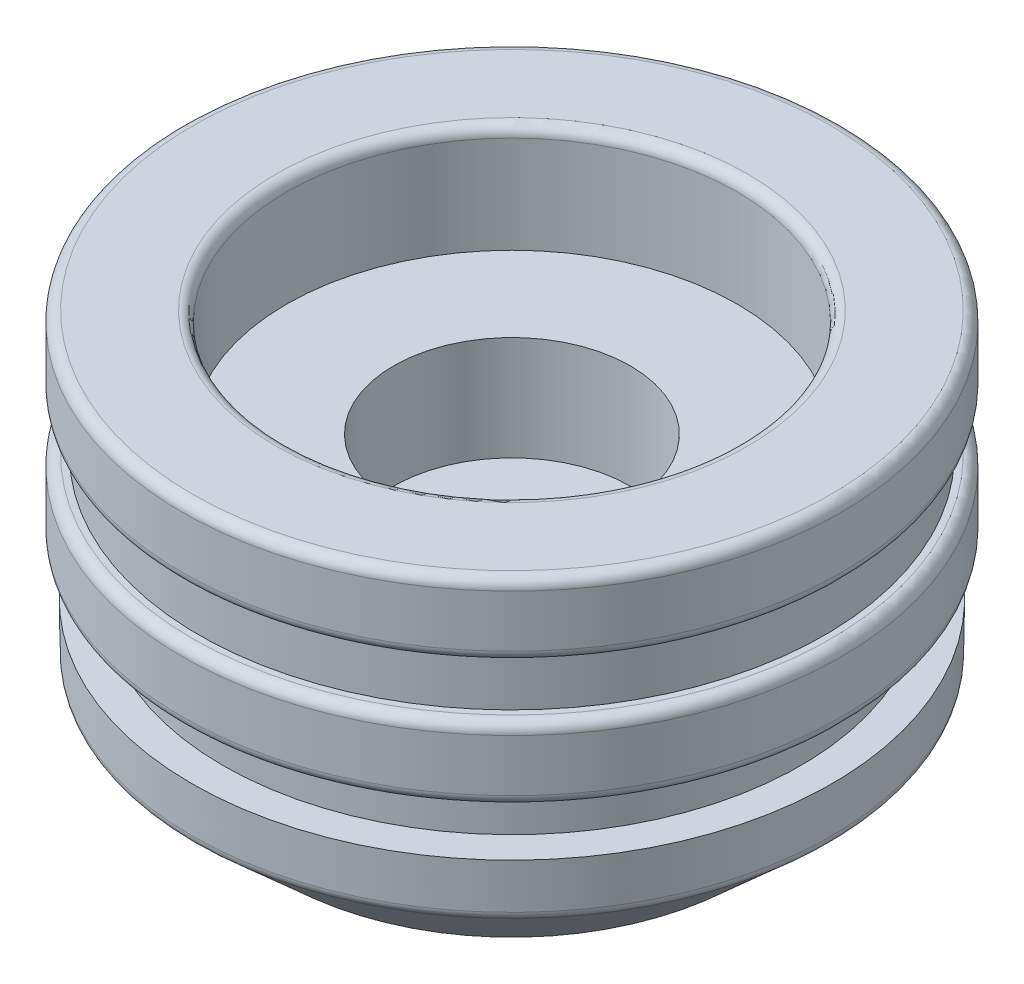
SolidWorks part; units mm, degrees
material "Silicon Rubber"
ref_plane "Front Plane" through (0, 0, 0) normal (0, 0, 1) x (1, 0, 0)
ref_plane "Top Plane" through (0, 0, 0) normal (0, 1, 0) x (1, 0, 0)
ref_plane "Right Plane" through (0, 0, 0) normal (1, 0, 0) x (0, 0, -1)
sketch "Sketch1" plane through (0, 0, 0) normal (0, 0, 1) x (1, 0, 0)
  line L1 (-3.446, 2.111) -> (-3.446, 1.611)
  line L10 (-3.8367, -0.189) -> (-3.5367, -0.189)
  line L13 (-3.546, 1.511) -> (-3.6059, 1.511)
  line L15 (-5.4719, 0.1791) -> (-5.4719, 1.1791)
  line L16 (-5.4719, 1.1791) -> (-4.446, 1.1791)
  line L17 (-4.446, 1.1791) -> (-4.446, 2.111)
  line L18 (-4.346, 2.211) -> (-3.546, 2.211)
  line L21 (-3.8367, -0.189) -> (-3.8367, 0.311)
  line L22 (-3.8367, 0.311) -> (-3.546, 0.311)
  line L23 (-3.446, 0.411) -> (-3.446, 0.911)
  line L24 (-3.6059, 1.011) -> (-3.546, 1.011)
  line L25 (-3.6059, 1.511) -> (-3.6059, 1.011)
  line L26 (-6.6085, -1.438) -> (-6.6085, 2.562) construction
  line L28 (-3.5762, -0.7003) -> (-4.3974, -1.438)
  line L29 (-5.4719, 0.1791) -> (-6.6085, 0.1791)
  line L30 (-6.6085, 0.1791) -> (-6.6085, -1.438)
  line L31 (-6.6085, -1.438) -> (-4.3974, -1.438)
  line L32 (-6.6085, -0.6295) -> (-2.6085, -0.6295) construction
  line L33 (-3.5367, -0.189) -> (-3.543, -0.6273)
  arc A2 (-3.546, 0.311) -> (-3.446, 0.411) centre (-3.546, 0.411) ccw
  arc A3 (-3.446, 0.911) -> (-3.546, 1.011) centre (-3.546, 0.911) ccw
  arc A4 (-3.446, 1.611) -> (-3.546, 1.511) centre (-3.546, 1.611) cw
  arc A5 (-4.446, 2.111) -> (-4.346, 2.211) centre (-4.346, 2.111) cw
  arc A6 (-3.546, 2.211) -> (-3.446, 2.111) centre (-3.546, 2.111) cw
  arc A7 (-3.5762, -0.7003) -> (-3.543, -0.6273) centre (-3.643, -0.6259) ccw
  dimension "D11" = 0.1
  dimension "D2" = 4
  dimension "D4" = 0.5
  dimension "D6" = 0.8
  dimension "D7" = 1
  dimension "D8" = 0.9319
  dimension "D9" = 0.5
  dimension "D10" = 0.5
  dimension "D14" = 1.026
  dimension "D16" = 0.0599
revolve "Revolve2" add sketch "Sketch1" angle 360 about L26
equation "\"Barrel Length\"= 55"
equation "\"Barrel Diameter\" = 10"
equation "\"Plunger Height\"= 1mm"
equation "\"Plunger Diameter\" = 5"
equation "\"Tip Height\" = 9"
equation "\"Tip Angle\" = 6"
equation "\"Finger Distance\" = 9"
equation "\"Finger Diameter\" = 6"
equation "\"Wall Thickness\" = 0.8"
